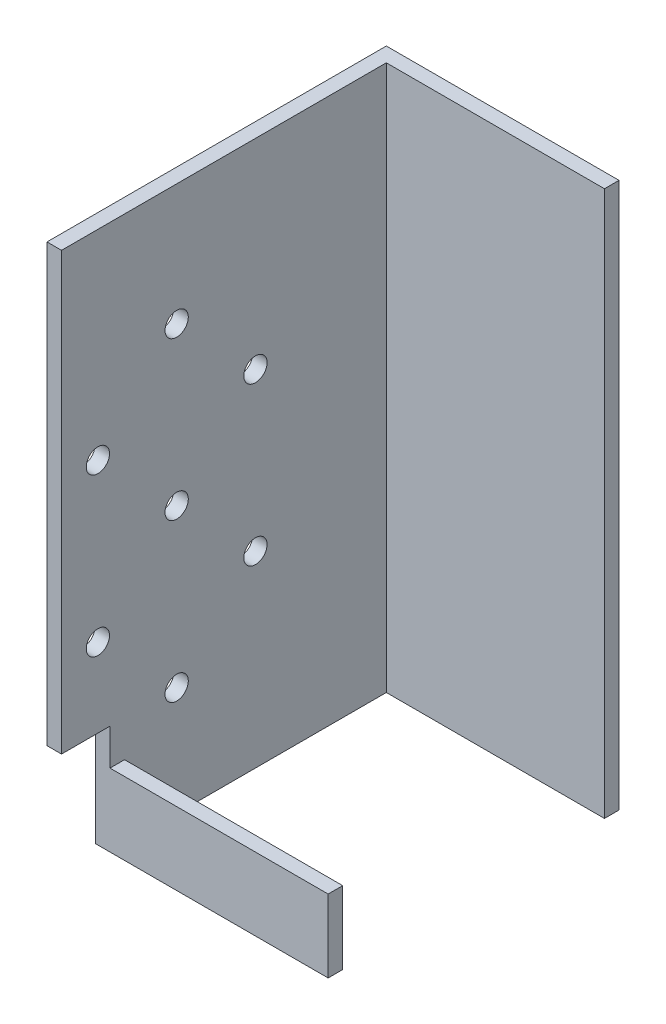
SolidWorks part; units mm, degrees
ref_plane "Front Plane" through (0, 0, 0) normal (0, 0, 1) x (1, 0, 0)
ref_plane "Top Plane" through (0, 0, 0) normal (0, 1, 0) x (1, 0, 0)
ref_plane "Right Plane" through (0, 0, 0) normal (1, 0, 0) x (0, 0, -1)
sketch "Sketch1" plane through (0, 0, 0) normal (1, 0, 0) x (0, 0, -1)
  line L1 (0, 0) -> (30.48, 0)
  line L2 (0, 0) -> (0, 57.15)
  line L3 (0, 57.15) -> (30.48, 57.15)
  line L4 (30.48, 0) -> (30.48, 57.15)
  dimension "D1" = 30.48
  dimension "D2" = 57.15
extrude "Boss-Extrude1" add sketch "Sketch1" along normal blind 1.524
sketch "Sketch2" plane through (1.524, 0, 0) normal (1, 0, 0) x (0, 0, -1)
  line L0 (30.48, 57.15) -> (0, 57.15) construction
  line L1 (30.48, 0) -> (28.956, 0)
  line L2 (30.48, 0) -> (30.48, 57.15)
  line L3 (30.48, 57.15) -> (28.956, 57.15)
  line L4 (28.956, 0) -> (28.956, 57.15)
  line L6 (0, 0) -> (1.524, 0)
  line L7 (0, 0) -> (0, 7.62)
  line L8 (0, 7.62) -> (1.524, 7.62)
  line L9 (1.524, 0) -> (1.524, 7.62)
  dimension "D1" = 1.524
  dimension "D2" = 1.524
  dimension "D3" = 7.62
extrude "Boss-Extrude2" add sketch "Sketch2" along normal blind 22.86
sketch "Sketch3" plane through (0, 0, 0) normal (0, 0, 1) x (1, 0, 0)
  line L0 (0, 57.15) -> (0, 0) construction
  line L1 (1.524, 57.15) -> (0, 57.15)
  line L2 (1.524, 57.15) -> (1.524, 11.43)
  line L3 (1.524, 11.43) -> (0, 11.43)
  line L4 (0, 57.15) -> (0, 11.43)
  dimension "D1" = 45.72
extrude "Boss-Extrude3" add sketch "Sketch3" along normal blind 5.08
hole_wizard "#2 Clearance Hole1" positions "Sketch5" profile "Sketch4" hole size "#2" standard "ANSI Inch" end condition through all
sketch "Sketch5" plane through (1.524, 0, 0) normal (1, 0, 0) x (0, 0, -1)
  line L0 (-5.08, 11.43) -> (-5.08, 57.15) construction
  line L1 (1.524, 0) -> (28.956, 0) construction
  point P0 (-1.27, 36.195)
  point P2 (15.24, 36.195)
  point P4 (6.985, 44.45)
  point P6 (6.985, 27.94)
  point P14 (6.985, 11.43)
  point P16 (15.24, 19.685)
  point P18 (-1.27, 19.685)
  dimension "D1" = 3.81
  dimension "D2" = 16.51
  dimension "D3" = 27.94
  dimension "D4" = 16.51
  dimension "D5" = 8.255
  dimension "D6" = 8.255
  dimension "D7" = 8.255
  dimension "D8" = 16.51
  dimension "D9" = 16.51
  dimension "D10" = 8.255
sketch "Sketch4" plane through (1.524, 36.195, 1.27) normal (0, 1, 0) x (0, 0, -1)
  line L0 (0, 0) -> (0, 1.524)
  line L1 (0, 1.524) -> (1.2192, 1.524)
  line L2 (1.2192, 1.524) -> (1.2192, 0)
  line L5 (1.2192, 0) -> (0, 0)
  line L11 (0, -6.35) -> (0, 107.95) construction
  dimension "Thru Hole Dia." = 2.4384
  dimension "Thru Hole Depth" = 1.524
